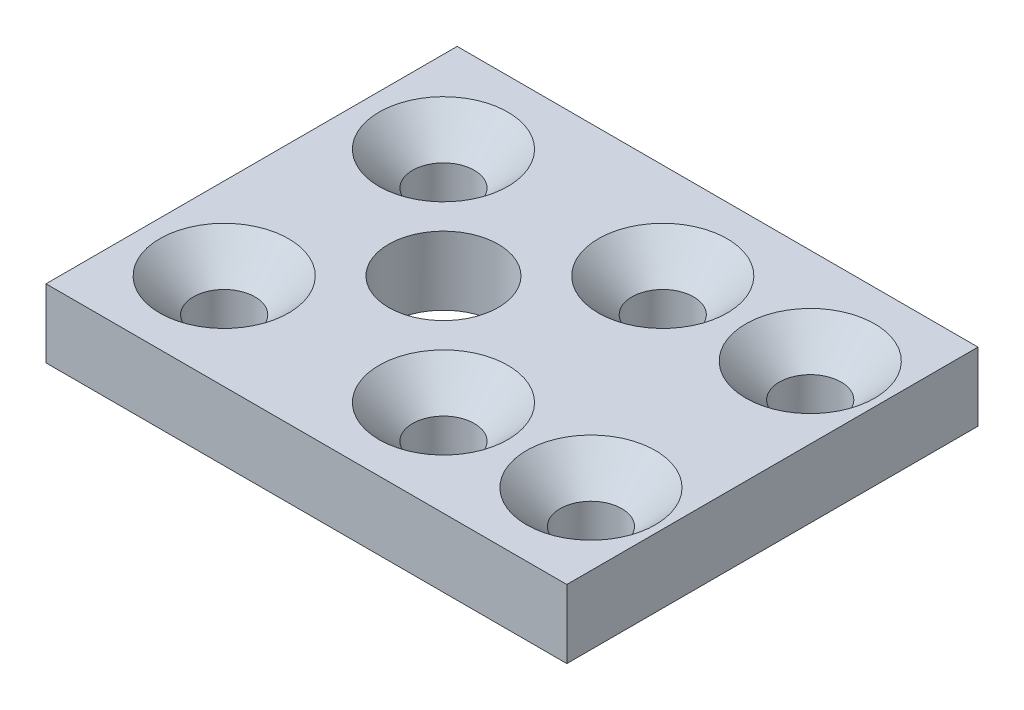
SolidWorks part; units mm, degrees
ref_plane "Ebene vorne" through (0, 0, 0) normal (0, 0, 1) x (1, 0, 0)
ref_plane "Ebene oben" through (0, 0, 0) normal (0, 1, 0) x (1, 0, 0)
ref_plane "Ebene rechts" through (0, 0, 0) normal (1, 0, 0) x (0, 0, -1)
sketch "Skizze1" plane through (0, 0, 0) normal (0, 1, 0) x (1, 0, 0)
  line L1 (-19, -15) -> (19, -15)
  line L2 (-19, -15) -> (-19, 15)
  line L3 (-19, 15) -> (19, 15)
  line L4 (19, -15) -> (19, 15)
  line L5 (-19, -15) -> (19, 15) construction
  line L6 (-19, 15) -> (19, -15) construction
  point P0 (0, 0)
  dimension "D1" = 30
  dimension "D2" = 38
extrude "Aufsatz-Linear austragen1" add sketch "Skizze1" along normal blind 5
hole_wizard "Formsenkung für M4 Senkschraube mit Schlitz/Kreuzschlitz1" positions "Skizze6" profile "Skizze7" countersink size "M4" standard "DIN" end condition up to next
sketch "Skizze6" plane through (0, 5, 0) normal (0, 1, 0) x (1, 0, 0)
  line L0 (-19, 15) -> (-19, -15) construction
  line L1 (-19, 0) -> (0, 0) construction
  line L2 (19, -15) -> (19, 15) construction
  point P0 (-13, 8)
  point P2 (3, 8)
  point P4 (3, -8)
  point P6 (-13, -8)
  point P21 (13.76, 8)
  point P23 (13.76, -8)
  dimension "D1" = 16
  dimension "D2" = 16
  dimension "D3" = 6
  dimension "D4" = 5.24
sketch "Skizze7" plane through (-13, 5, -8) normal (1, 0, 0) x (0, 0, 1)
  line L0 (0, 0) -> (0, 5)
  line L1 (0, 5) -> (2.25, 5)
  line L2 (2.25, 5) -> (2.25, 2.45)
  line L3 (2.25, 2.45) -> (4.7, 0)
  line L5 (4.7, 0) -> (0, 0)
  line L6 (-2.25, 2.45) -> (-4.7, 0) construction
  line L11 (0, -6.35) -> (0, 107.95) construction
  dimension "Bohrerdurchmesser" = 4.5
  dimension "Bohrungstiefe" = 5
  dimension "Senkdurchmesser (Oben)" = 9.4
  dimension "Senkwinkel (Oben)" = 90
hole_wizard "Ø8.0 (8) Durchmesser Bohrung1" positions "Skizze10" profile "Skizze9" hole size "Ø8.0" standard "DIN" end condition up to next
sketch "Skizze10" plane through (0, 5, 0) normal (0, 1, 0) x (1, 0, 0)
  point P0 (-5, 0)
  dimension "D1" = 5
sketch "Skizze9" plane through (-5, 5, 0) normal (1, 0, 0) x (0, 0, 1)
  line L0 (0, 0) -> (0, 5)
  line L1 (0, 5) -> (4, 5)
  line L2 (4, 5) -> (4, 0)
  line L5 (4, 0) -> (0, 0)
  line L11 (0, -6.35) -> (0, 107.95) construction
  dimension "Bohrerdurchmesser" = 8
  dimension "Bohrungstiefe" = 5
